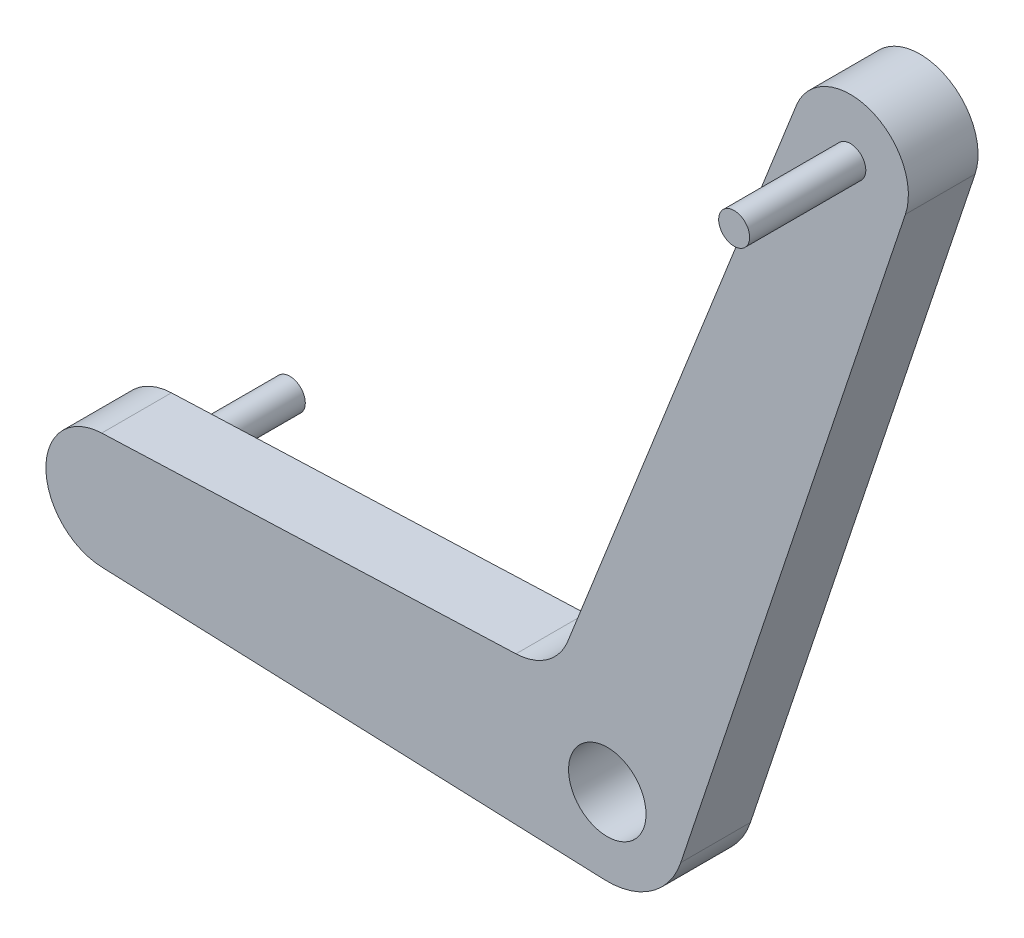
SolidWorks part; units mm, degrees
ref_plane "前视基准面" through (0, 0, 0) normal (0, 0, 1) x (1, 0, 0)
ref_plane "上视基准面" through (0, 0, 0) normal (0, 1, 0) x (1, 0, 0)
ref_plane "右视基准面" through (0, 0, 0) normal (1, 0, 0) x (0, 0, -1)
other "Configuration Table"
sketch "草图1" plane through (0, 0, 0) normal (0, 0, 1) x (1, 0, 0)
  line L0 (-130, 0) -> (0, 0) construction
  line L1 (0, 0) -> (62.7607, 172.4336) construction
  line L2 (-0.7692, -19.9852) -> (-130.5769, -14.9889)
  line L3 (18.9733, -6.3258) -> (76.9906, 167.6893)
  line L4 (48.8103, 177.9461) -> (-10.2101, 28.5835)
  line L5 (-130.5769, 14.9889) -> (-23.5835, 19.1071)
  arc A0 (-0.7692, -19.9852) -> (18.9733, -6.3258) centre (0, 0) ccw
  arc A1 (-130.5769, 14.9889) -> (-130.5769, -14.9889) centre (-130, 0) ccw
  arc A2 (76.9906, 167.6893) -> (48.8103, 177.9461) centre (62.7607, 172.4336) ccw
  arc A3 (-10.2101, 28.5835) -> (-23.5835, 19.1071) centre (-24.1604, 34.096) cw
  dimension "D1" = 15
extrude "凸台-拉伸1" add sketch "草图1" along normal blind 18
sketch "草图2" plane through (0, 0, 0) normal (0, 0, 1) x (1, 0, 0)
  circle A0 centre (0, 0) radius 10
extrude "切除-拉伸1" cut sketch "草图2" along normal blind 18
sketch "草图3" plane through (0, 0, 0) normal (0, 0, 1) x (1, 0, 0)
  circle A0 centre (-130, 0) radius 4
extrude "凸台-拉伸2" add sketch "草图3" against normal blind 30
sketch "草图4" plane through (0, 0, 18) normal (0, 0, 1) x (1, 0, 0)
  circle A0 centre (62.7607, 172.4336) radius 4
extrude "凸台-拉伸3" add sketch "草图4" along normal blind 30
